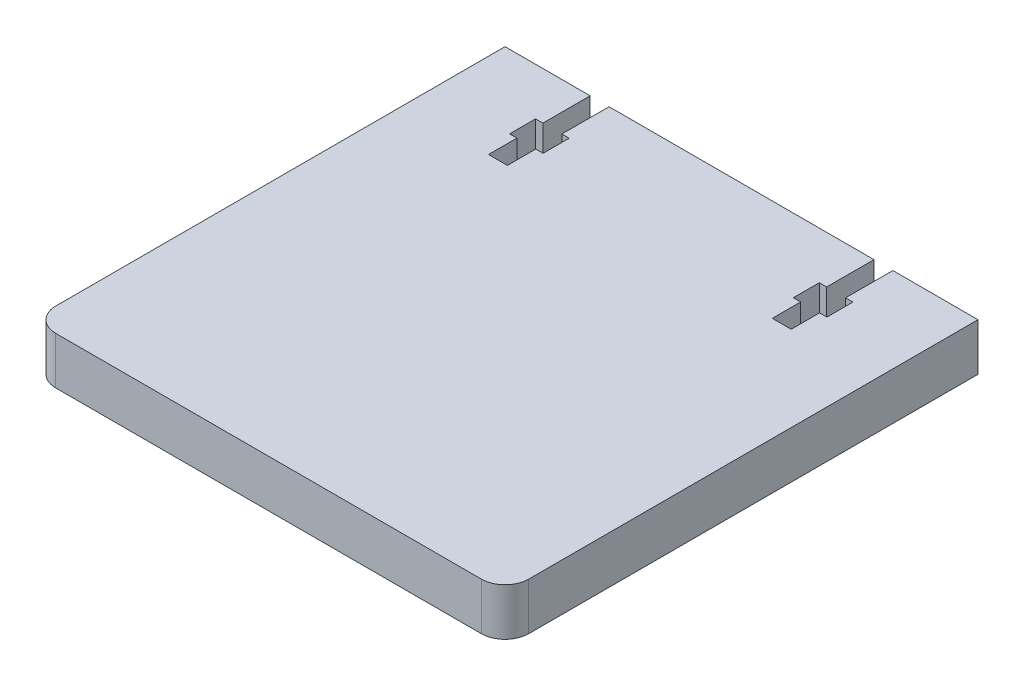
SolidWorks part; units mm, degrees
ref_plane "Front Plane" through (0, 0, 0) normal (0, 0, 1) x (1, 0, 0)
ref_plane "Top Plane" through (0, 0, 0) normal (0, 1, 0) x (1, 0, 0)
ref_plane "Right Plane" through (0, 0, 0) normal (1, 0, 0) x (0, 0, -1)
sketch "Sketch1" plane through (0, 0, 0) normal (0, 0, 1) x (1, 0, 0)
  line L1 (0, 0) -> (100, 0)
  line L2 (0, 0) -> (0, 10)
  line L3 (0, 10) -> (100, 10)
  line L4 (100, 0) -> (100, 10)
  dimension "D1" = 100
  dimension "D2" = 10
extrude "Boss-Extrude1" add sketch "Sketch1" along normal blind 100
sketch "Esquisse1" plane through (0, 0, 0) normal (0, -1, 0) x (1, 0, 0)
  line L0 (18, 0) -> (18, 10)
  line L1 (0, 0) -> (100, 0) construction
  line L2 (18, 10) -> (16.45, 10)
  line L3 (16.45, 10) -> (16.45, 15.5)
  line L4 (16.45, 15.5) -> (18, 15.5)
  line L5 (18, 15.5) -> (18, 21.5)
  line L6 (18, 21.5) -> (22, 21.5)
  line L7 (18, 0) -> (22, 0)
  line L8 (20, 21.5) -> (20, 0) construction
  line L9 (0, 100) -> (0, 0) construction
  line L10 (22, 15.5) -> (22, 21.5)
  line L11 (23.55, 15.5) -> (22, 15.5)
  line L12 (23.55, 10) -> (23.55, 15.5)
  line L13 (22, 10) -> (23.55, 10)
  line L14 (22, 0) -> (22, 10)
  line L15 (50, 100) -> (50, 0) construction
  line L16 (0, 100) -> (100, 100) construction
  line L17 (18, 0) -> (18, 10)
  line L18 (18, 10) -> (16.45, 10)
  line L19 (16.45, 10) -> (16.45, 15.5)
  line L20 (16.45, 15.5) -> (18, 15.5)
  line L21 (18, 15.5) -> (18, 21.5)
  line L22 (22, 15.5) -> (22, 21.5)
  line L23 (23.55, 15.5) -> (22, 15.5)
  line L24 (23.55, 10) -> (23.55, 15.5)
  line L25 (22, 10) -> (23.55, 10)
  line L26 (22, 0) -> (22, 10)
  line L27 (80, 21.5) -> (80, 0) construction
  line L28 (78, 0) -> (78, 10)
  line L29 (78, 10) -> (76.45, 10)
  line L30 (76.45, 10) -> (76.45, 15.5)
  line L31 (76.45, 15.5) -> (78, 15.5)
  line L32 (78, 15.5) -> (78, 21.5)
  line L33 (82, 15.5) -> (82, 21.5)
  line L34 (83.55, 15.5) -> (82, 15.5)
  line L35 (83.55, 10) -> (83.55, 15.5)
  line L36 (82, 10) -> (83.55, 10)
  line L37 (82, 0) -> (82, 10)
  line L38 (78, 0) -> (78, 10)
  line L39 (78, 10) -> (76.45, 10)
  line L40 (76.45, 10) -> (76.45, 15.5)
  line L41 (76.45, 15.5) -> (78, 15.5)
  line L42 (78, 15.5) -> (78, 21.5)
  line L43 (82, 0) -> (78, 0)
  line L44 (82, 21.5) -> (78, 21.5)
  line L45 (82, 15.5) -> (82, 21.5)
  line L46 (83.55, 15.5) -> (82, 15.5)
  line L47 (83.55, 10) -> (83.55, 15.5)
  line L48 (82, 10) -> (83.55, 10)
  line L49 (82, 0) -> (82, 10)
  line M6 (0, 0) -> (100, 0)
  dimension "D1" = 2
  dimension "D2" = 2
  dimension "D3" = 5.5
  dimension "D4" = 10
  dimension "D5" = 6
  dimension "D6" = 20
  dimension "D7" = 7.1
extrude "Enlèv. mat.-Extru.1" cut sketch "Esquisse1" against normal blind 10 contours L14 L13 L12 L11 L10 L6 L5 L4 L3 L2 L0 M6 | L33 L44 L32 L31 L30 L29 L28 L37 L36 L35 L34 M6
fillet "Congé1" radius 5 1 edges at (0, 5, 100)
fillet "Congé3" radius 5 1 edges at (100, 5, 100)
